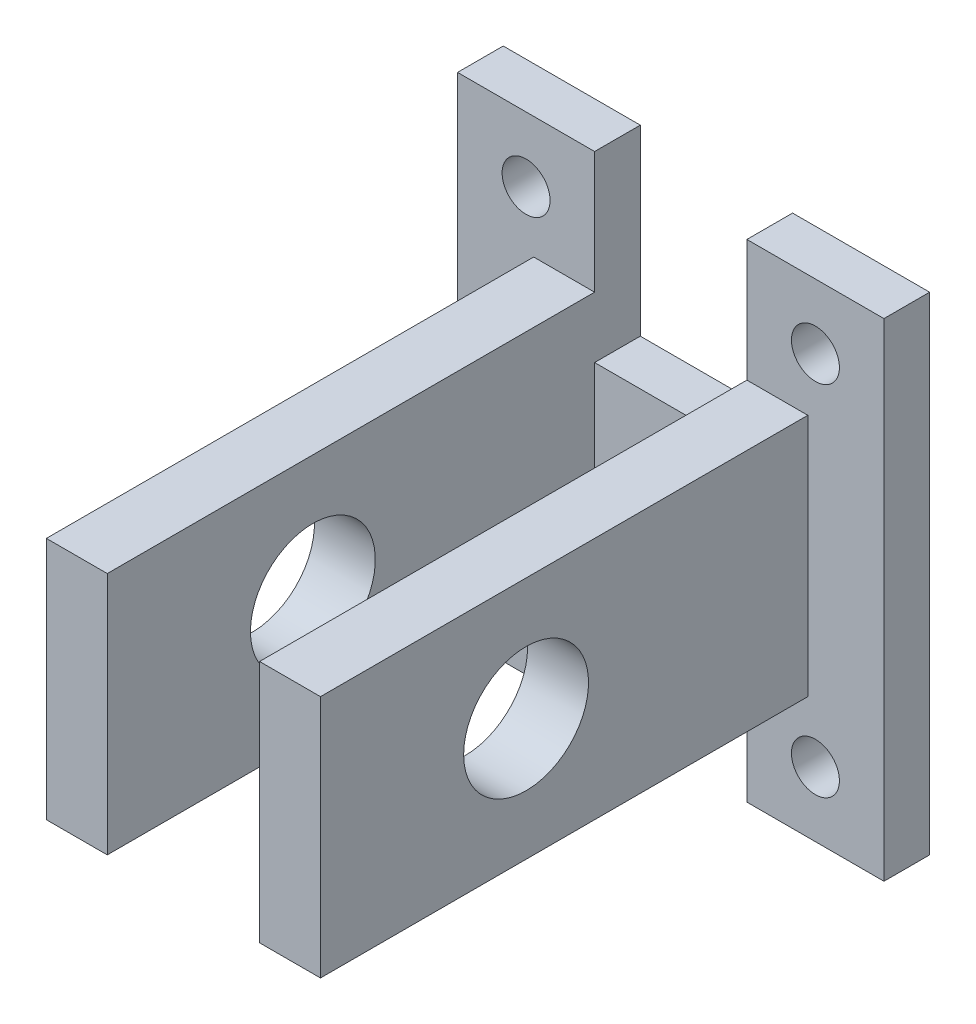
SolidWorks part; units mm, degrees
ref_plane "Front Plane" through (0, 0, 0) normal (0, 0, 1) x (1, 0, 0)
ref_plane "Top Plane" through (0, 0, 0) normal (0, 1, 0) x (1, 0, 0)
ref_plane "Right Plane" through (0, 0, 0) normal (1, 0, 0) x (0, 0, -1)
sketch "Sketch1" plane through (0, 0, 0) normal (0, 0, 1) x (1, 0, 0)
  line L0 (0, 0) -> (0, 32)
  line L1 (0, 32) -> (9, 32)
  line L2 (9, 32) -> (9, 20)
  line L3 (9, 20) -> (19, 20)
  line L4 (19, 20) -> (19, 32)
  line L5 (19, 32) -> (28, 32)
  line L6 (28, 32) -> (28, 0)
  line L7 (28, 0) -> (19, 0)
  line L8 (19, 0) -> (19, 12)
  line L9 (19, 12) -> (9, 12)
  line L10 (9, 12) -> (9, 0)
  line L11 (9, 0) -> (0, 0)
  line L12 (14, -991) -> (14, 49009) construction
  circle A0 centre (4.5, 27.75) radius 1.575
  circle A1 centre (4.5, 4.25) radius 1.575
  circle A2 centre (23.5, 4.25) radius 1.575
  circle A3 centre (23.5, 27.75) radius 1.575
  point P16 (4.5, 32)
  point P24 (14, 12)
  dimension "D9" = 3.15
  dimension "D10" = 3.15
  dimension "D1" = 32
  dimension "D2" = 9
  dimension "D3" = 9
  dimension "D4" = 10
  dimension "D5" = 10
  dimension "D6" = 9
  dimension "D7" = 12
  dimension "D8" = 12
  dimension "D11" = 4.25
  dimension "D12" = 4.25
extrude "Boss-Extrude1" add sketch "Sketch1" along normal blind 3
sketch "Sketch2" plane through (0, 0, 3) normal (0, 0, 1) x (1, 0, 0)
  line L0 (9, 24) -> (5, 24)
  line L1 (9, 20) -> (9, 32) construction
  line L2 (5, 24) -> (5, 8)
  line L3 (5, 8) -> (9, 8)
  line L4 (9, 0) -> (9, 12) construction
  line L5 (9, 8) -> (9, 24)
  line L6 (19, 24) -> (23, 24)
  line L7 (19, 32) -> (19, 20) construction
  line L8 (23, 24) -> (23, 8)
  line L9 (23, 8) -> (19, 8)
  line L10 (19, 8) -> (19, 24)
  line L11 (0, 32) -> (0, 0) construction
  line L12 (28, 0) -> (28, 32) construction
  point P12 (5, 16)
  point P17 (0, 16)
  point P18 (23, 16)
  point P21 (28, 16)
  dimension "D1" = 4
  dimension "D2" = 16
  dimension "D3" = 4
extrude "Boss-Extrude2" add sketch "Sketch2" along normal blind 32
sketch "Sketch3" plane through (5, 0, 0) normal (-1, 0, 0) x (0, 0, 1)
  line L0 (35, 24) -> (35, 8) construction
  circle A0 centre (21.5, 16) radius 4.1
  point P2 (0, 0)
  point P5 (0, 0)
  point P6 (0, 0)
  point P7 (35, 16)
  dimension "D1" = 8.2
  dimension "D2" = 13.5
extrude "Cut-Extrude1" cut sketch "Sketch3" against normal blind 35
